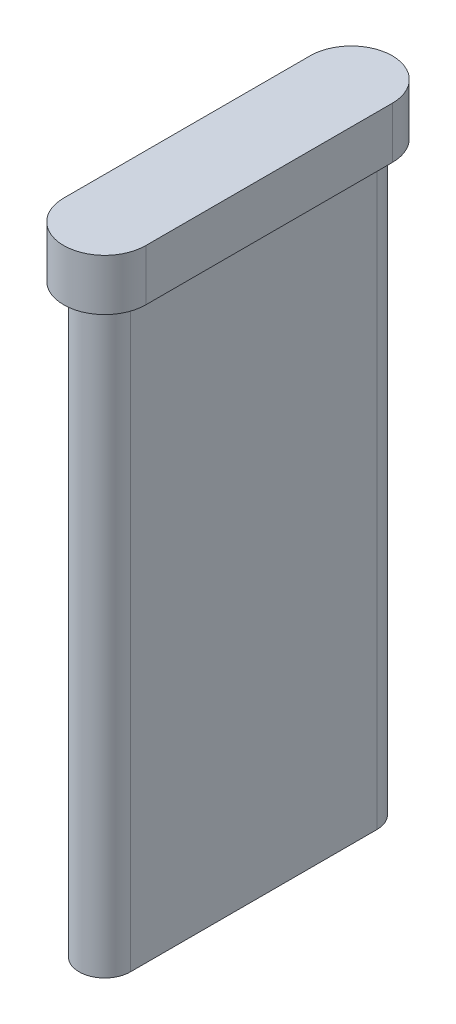
SolidWorks part; units mm, degrees
material "K110"
ref_plane "Front Plane" through (0, 0, 0) normal (0, 0, 1) x (1, 0, 0)
ref_plane "Top Plane" through (0, 0, 0) normal (0, 1, 0) x (1, 0, 0)
ref_plane "Right Plane" through (0, 0, 0) normal (1, 0, 0) x (0, 0, -1)
sketch "Sketch1" plane through (0, 0, 0) normal (0, 1, 0) x (1, 0, 0)
  line L0 (0, -12) -> (0, 12) construction
  line L1 (-2.5, -12) -> (-2.5, 12)
  line L2 (2.5, -12) -> (2.5, 12)
  arc A0 (-2.5, -12) -> (2.5, -12) centre (0, -12) ccw
  arc A1 (2.5, 12) -> (-2.5, 12) centre (0, 12) ccw
  point P2 (0, 0)
  dimension "D2" = 2.5
  dimension "D1" = 24
extrude "Boss-Extrude1" add sketch "Sketch1" against normal blind 62
sketch "Sketch2" plane through (0, 0, 0) normal (0, 1, 0) x (1, 0, 0)
  line L4 (4, -12) -> (4, 12)
  line L5 (-4, 12) -> (-4, -12)
  line L6 (4, -12) -> (4, 12)
  line L7 (-4, 12) -> (-4, -12)
  arc A4 (4, 12) -> (-4, 12) centre (0, 12) ccw
  arc A5 (-4, -12) -> (4, -12) centre (0, -12) ccw
  arc A6 (4, 12) -> (-4, 12) centre (0, 12) ccw
  arc A7 (-4, -12) -> (4, -12) centre (0, -12) ccw
  dimension "D1" = 1.5
extrude "Boss-Extrude2" add sketch "Sketch2" against normal blind 5
